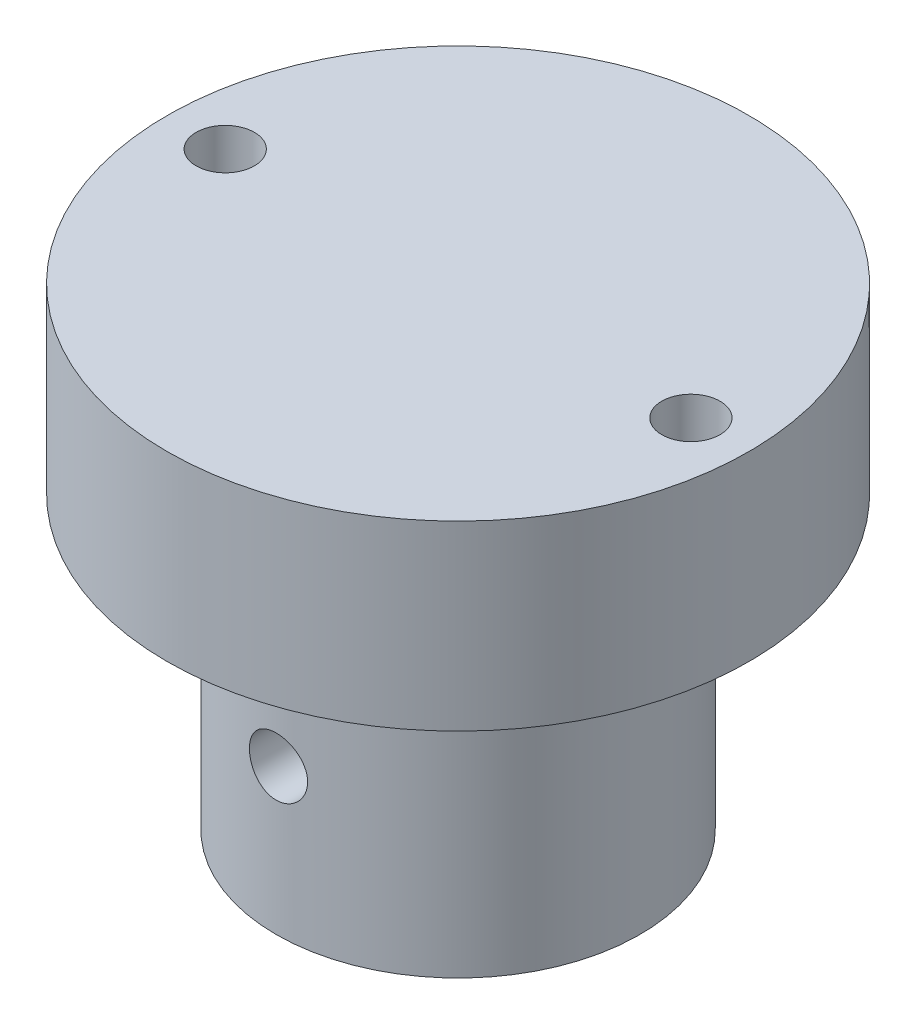
SolidWorks part; units mm, degrees
ref_plane "Front Plane" through (0, 0, 0) normal (0, 0, 1) x (1, 0, 0)
ref_plane "Top Plane" through (0, 0, 0) normal (0, 1, 0) x (1, 0, 0)
ref_plane "Right Plane" through (0, 0, 0) normal (1, 0, 0) x (0, 0, -1)
sketch "Sketch1" plane through (0, 0, 0) normal (0, 1, 0) x (1, 0, 0)
  circle A0 centre (0, 0) radius 6.35
  dimension "D1" = 12.7
extrude "Boss-Extrude1" add sketch "Sketch1" along normal blind 10.16
sketch "Sketch2" plane through (0, 10.16, 0) normal (0, 1, 0) x (1, 0, 0)
  circle A0 centre (0, 0) radius 4.7625
  dimension "D1" = 9.525
extrude "Cut-Extrude2" cut sketch "Sketch2" against normal up to surface (10.16 mm away) up to face at (0, 0, 6.35)
sketch "Sketch3" plane through (0, 10.16, 0) normal (0, 1, 0) x (1, 0, 0)
  circle A0 centre (0, 0) radius 6.35
  dimension "D1" = 12.7
extrude "Boss-Extrude2" add sketch "Sketch3" along normal blind 6.35
sketch "Sketch4" plane through (0, 0, 0) normal (0, 0, 1) x (1, 0, 0)
  line L0 (-4.7625, 0) -> (4.7625, 0) construction
  circle A0 centre (0, 5.08) radius 1.016
  point P5 (0, 0)
  dimension "D1" = 2.032
  dimension "D2" = 5.08
extrude "Cut-Extrude3" cut sketch "Sketch4" against normal up to surface and the other way up to surface up to face at (0, 0, 6.35) other way up to face at (0, 0, 6.35)
sketch "Sketch5" plane through (0, 16.51, 0) normal (0, 1, 0) x (1, 0, 0)
  circle A0 centre (0, 0) radius 10.16
  circle A1 centre (0, 0) radius 6.35
  dimension "D1" = 20.32
  dimension "D2" = 12.7
extrude "Boss-Extrude3" add sketch "Sketch5" against normal blind 6.35
sketch "Sketch10" plane through (0, 16.51, 0) normal (0, 1, 0) x (1, 0, 0)
  circle A0 centre (8.128, 0) radius 1.016
  circle A1 centre (-8.128, 0) radius 1.016
  circle A3 centre (0, 0) radius 10.16 construction
  point P4 (0, 0)
  dimension "D1" = 2.032
  dimension "D2" = 2.032
  dimension "D3" = 8.128
  dimension "D4" = 8.128
  dimension "D5" = 16.256
extrude "Cut-Extrude4" cut sketch "Sketch10" against normal up to surface (6.35 mm away) up to face at (0, 10.16, 6.35)
